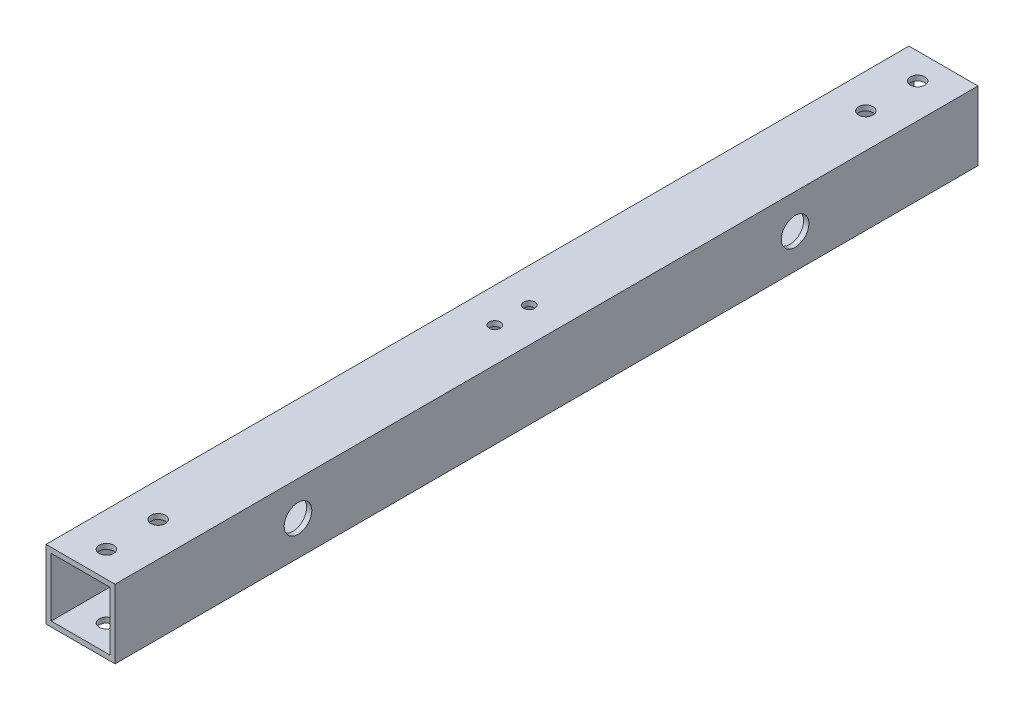
SolidWorks part; units mm, degrees
ref_plane "前视基准面" through (0, 0, 0) normal (0, 0, 1) x (1, 0, 0)
ref_plane "上视基准面" through (0, 0, 0) normal (0, 1, 0) x (1, 0, 0)
ref_plane "右视基准面" through (0, 0, 0) normal (1, 0, 0) x (0, 0, -1)
sketch "草图1" plane through (0, 0, 0) normal (0, 0, 1) x (1, 0, 0)
  line L0 (-8.5, 8.5) -> (8.5, 8.5)
  line L1 (-10, -10) -> (10, -10)
  line L2 (-10, -10) -> (-10, 10)
  line L3 (-10, 10) -> (10, 10)
  line L4 (10, -10) -> (10, 10)
  line L5 (-10, -10) -> (10, 10) construction
  line L6 (-10, 10) -> (10, -10) construction
  line L7 (8.5, -8.5) -> (8.5, 8.5)
  line L8 (-8.5, -8.5) -> (8.5, -8.5)
  line L9 (-8.5, -8.5) -> (-8.5, 8.5)
  point P0 (0, 0)
  dimension "D1" = 20
  dimension "D2" = 20
  dimension "D3" = 1.5
extrude "凸台-拉伸1" add sketch "草图1" along normal blind 250
sketch "草图2" plane through (0, 10, 0) normal (0, 1, 0) x (1, 0, 0)
  line L0 (0, 0) -> (0, -50000) construction
  line L1 (10, 0) -> (-10, 0) construction
  line L2 (10, -125) -> (50010, -125) construction
  line L3 (10, -250) -> (10, 0) construction
  circle A0 centre (0, -7.5) radius 2.1
  circle A1 centre (0, -22.5) radius 2.1
  circle A2 centre (0, -120) radius 1.6
  circle A3 centre (0, -130) radius 1.6
  circle A4 centre (0, -227.5) radius 2.1
  circle A5 centre (0, -242.5) radius 2.1
  point P13 (10, -125)
  dimension "D1" = 4.2
  dimension "D2" = 4.2
  dimension "D5" = 3.2
  dimension "D3" = 15
  dimension "D4" = 7.5
  dimension "D6" = 10
extrude "切除-拉伸1" cut sketch "草图2" against normal through all
sketch "草图3" plane through (-10, 0, 0) normal (-1, 0, 0) x (0, 0, 1)
  line L0 (0, 0) -> (50000, 0) construction
  line L1 (125, 10) -> (125, -49990) construction
  line L2 (250, 10) -> (0, 10) construction
  line L3 (250, 10) -> (250, -10) construction
  circle A0 centre (197, 0) radius 4
  circle A1 centre (53, 0) radius 4
  point P7 (125, 10)
  dimension "D1" = 8
  dimension "D2" = 53
extrude "切除-拉伸3" cut sketch "草图3" against normal through all
equation "\"4。2\"=5.92873"
